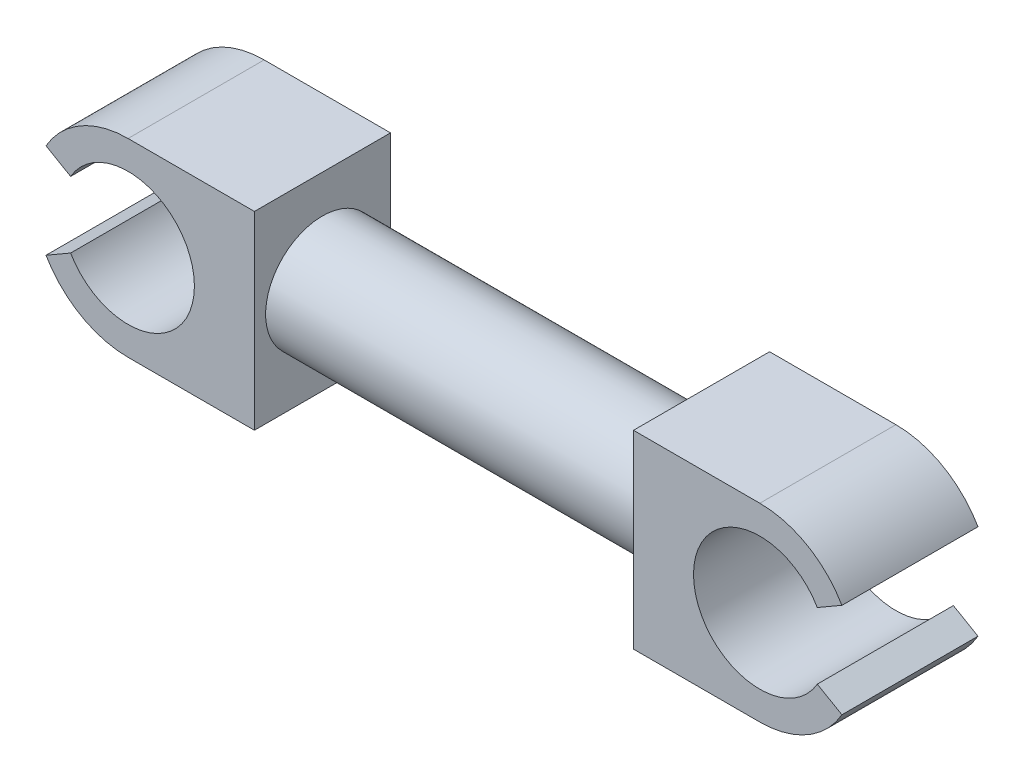
SolidWorks part; units mm, degrees
ref_plane "Piano frontale" through (0, 0, 0) normal (0, 0, 1) x (1, 0, 0)
ref_plane "Piano superiore" through (0, 0, 0) normal (0, 1, 0) x (1, 0, 0)
ref_plane "Piano destro" through (0, 0, 0) normal (1, 0, 0) x (0, 0, -1)
sketch "Schizzo1" plane through (0, 0, 0) normal (0, 0, 1) x (1, 0, 0)
  line L0 (0, 15) -> (100, 15)
  line L1 (0, -15) -> (100, -15)
  line L2 (0, 0) -> (-22.2873, 12.8676) construction
  line L3 (0, 0) -> (-24.0414, 0) construction
  line L4 (0, 0) -> (-22.6277, -13.0641) construction
  line L5 (-12.9904, -7.5) -> (-9.0933, -5.25)
  line L6 (-9.0933, 5.25) -> (-12.9904, 7.5)
  line L7 (50, -15) -> (50, 15) construction
  line L8 (112.9904, -7.5) -> (109.0933, -5.25)
  line L9 (109.0933, 5.25) -> (112.9904, 7.5)
  arc A0 (-9.0933, -5.25) -> (-9.0933, 5.25) centre (0, 0) ccw
  arc A1 (-12.9904, -7.5) -> (0, -15) centre (0, 0) ccw
  arc A2 (0, 15) -> (-12.9904, 7.5) centre (0, 0) ccw
  arc A3 (112.9904, -7.5) -> (100, -15) centre (100, 0) cw
  arc A4 (109.0933, -5.25) -> (109.0933, 5.25) centre (100, 0) cw
  arc A5 (100, 15) -> (112.9904, 7.5) centre (100, 0) cw
  point P1 (0, 0)
  point P21 (-63.9478, 31.9447)
  dimension "D1" = 21
  dimension "D2" = 30
  dimension "D4" = 100
  dimension "D5" = 30
  dimension "D6" = 30
extrude "Estrusione-Estrusione1" add sketch "Schizzo1" along normal blind 21.54
ref_plane "Piano1" through (20, 0, 0) normal (1, 0, 0) x (0, 0, -1)
sketch "Schizzo2" plane through (20, 0, 0) normal (1, 0, 0) x (0, 0, -1)
  line L0 (-21.54, 15) -> (0, 15) construction
  line L2 (0, -15) -> (-21.54, -15)
  line L3 (0, -15) -> (0, 15)
  line L4 (0, 15) -> (-21.54, 15)
  line L5 (-21.54, -15) -> (-21.54, 15)
  line L6 (0, -15) -> (-21.54, 15) construction
  line L7 (0, 15) -> (-21.54, -15) construction
  circle A0 centre (-10.77, 0) radius 9
  point P5 (-10.77, 15)
  dimension "D1" = 18
extrude "Taglio-Estrusione1" cut sketch "Schizzo2" along normal blind 60
